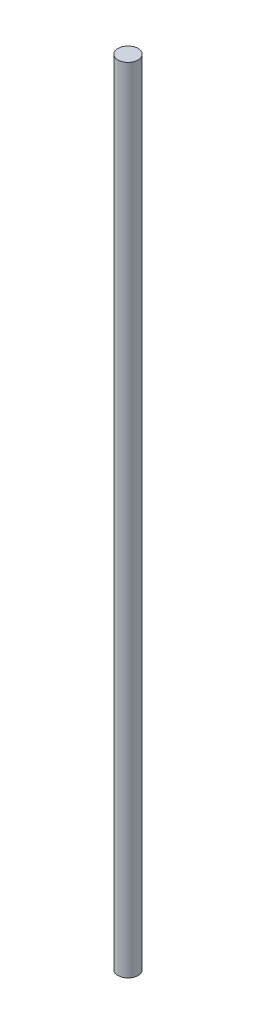
SolidWorks part; units mm, degrees
ref_plane "Front Plane" through (0, 0, 0) normal (0, 0, 1) x (1, 0, 0)
ref_plane "Top Plane" through (0, 0, 0) normal (0, 1, 0) x (1, 0, 0)
ref_plane "Right Plane" through (0, 0, 0) normal (1, 0, 0) x (0, 0, -1)
sketch "Sketch1" plane through (0, 0, 0) normal (0, 1, 0) x (1, 0, 0)
  circle A0 centre (-61.6436, 0) radius 10
  dimension "D1" = 20
extrude "Boss-Extrude2" add sketch "Sketch1" along normal blind 790
